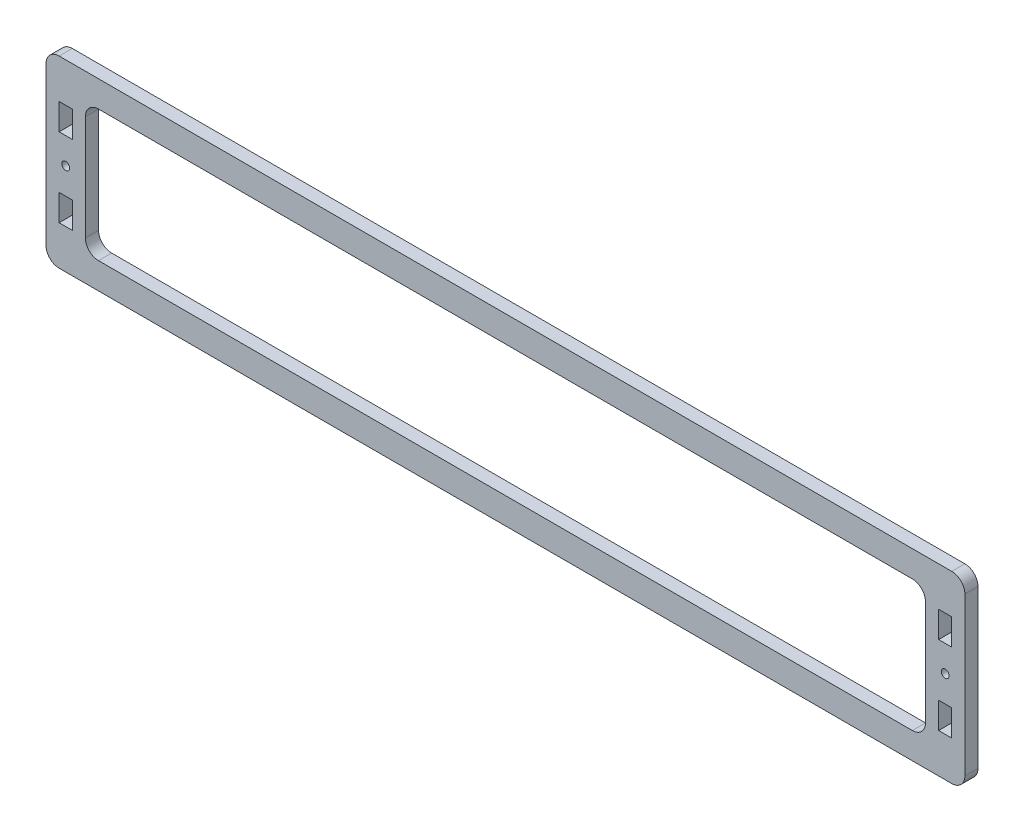
SolidWorks part; units mm, degrees
ref_plane "Front Plane" through (0, 0, 0) normal (0, 0, 1) x (1, 0, 0)
ref_plane "Top Plane" through (0, 0, 0) normal (0, 1, 0) x (1, 0, 0)
ref_plane "Right Plane" through (0, 0, 0) normal (1, 0, 0) x (0, 0, -1)
sketch "Sketch1" plane through (0, 0, 0) normal (0, 0, 1) x (1, 0, 0)
  line L0 (-90.218, 10) -> (299.3045, 10) construction
  line L1 (-85.8133, 35) -> (264.1867, 35)
  line L2 (-85.8133, 35) -> (-85.8133, -35)
  line L3 (-85.8133, -35) -> (264.1867, -35)
  line L4 (264.1867, 35) -> (264.1867, -35)
  line L5 (-80.8133, -10) -> (-75.8133, -10)
  line L6 (-91.3268, 0) -> (299.3045, 0) construction
  line L7 (-80.8133, 20) -> (-75.8133, 20)
  line L8 (-80.8133, 20) -> (-80.8133, 10)
  line L9 (-80.8133, 10) -> (-75.8133, 10)
  line L10 (-75.8133, 20) -> (-75.8133, 10)
  line L11 (-75.8133, -20) -> (-75.8133, -10)
  line L12 (-80.8133, -20) -> (-75.8133, -20)
  line L13 (-80.8133, -20) -> (-80.8133, -10)
  line L14 (89.1867, 30.0157) -> (89.1867, -45.8134) construction
  line L15 (-78.3133, 24.0051) -> (-78.3133, -32.23) construction
  line L16 (259.1867, -20) -> (259.1867, -10)
  line L17 (259.1867, -20) -> (254.1867, -20)
  line L18 (254.1867, -20) -> (254.1867, -10)
  line L19 (259.1867, -10) -> (254.1867, -10)
  line L20 (259.1867, 10) -> (254.1867, 10)
  line L21 (254.1867, 20) -> (254.1867, 10)
  line L22 (259.1867, 20) -> (254.1867, 20)
  line L23 (259.1867, 20) -> (259.1867, 10)
  circle A31 centre (-78.3133, 0) radius 1.5
  circle A32 centre (256.6867, 0) radius 1.5
  point P6 (89.1867, -35)
  point P13 (-85.8133, 0)
  point P82 (-78.3133, 20)
  dimension "D1" = 70
  dimension "D2" = 350
  dimension "D3" = 20
  dimension "D4" = 10
  dimension "D7" = 5
  dimension "D8" = 5
extrude "Boss-Extrude1" add sketch "Sketch1" along normal blind 5
sketch "Esquisse1" plane through (0, 0, 5) normal (0, 0, 1) x (1, 0, 0)
  line L0 (264.1867, 35) -> (-85.8133, 35) construction
  line L1 (-70.8133, 25) -> (249.1867, 25)
  line L2 (-70.8133, 25) -> (-70.8133, -25)
  line L3 (-70.8133, -25) -> (249.1867, -25)
  line L4 (249.1867, 25) -> (249.1867, -25)
  line L5 (-85.8133, -35) -> (264.1867, -35) construction
  line L6 (-75.8133, 10) -> (-75.8133, 20) construction
  line L7 (254.1867, 20) -> (254.1867, 10) construction
  dimension "D1" = 10
  dimension "D2" = 10
  dimension "D3" = 5
  dimension "D4" = 5
extrude "Enlèv. mat.-Extru.1" cut sketch "Esquisse1" against normal blind 10
fillet "Congé1" radius 5 8 edges at (249.1867, -25, 2.5) (-70.8133, -25, 2.5) (-70.8133, 25, 2.5) (249.1867, 25, 2.5) (-85.8133, -35, 2.5) (264.1867, 35, 2.5) (264.1867, -35, 2.5) (-85.8133, 35, 2.5)
